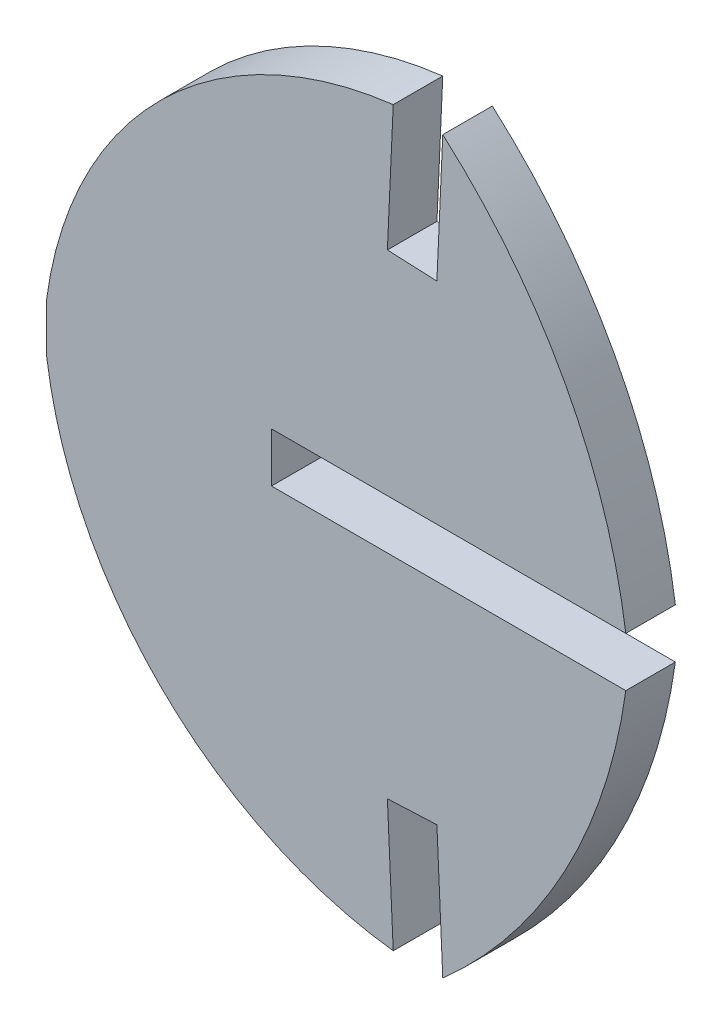
SolidWorks part; units mm, degrees
ref_plane "Front Plane" through (0, 0, 0) normal (0, 0, 1) x (1, 0, 0)
ref_plane "Top Plane" through (0, 0, 0) normal (0, 1, 0) x (1, 0, 0)
ref_plane "Right Plane" through (0, 0, 0) normal (1, 0, 0) x (0, 0, -1)
sketch "Sketch1" plane through (0, 0, 0) normal (0, 0, 1) x (1, 0, 0)
  line L0 (68.0534, 0) -> (68.0534, -1.524)
  line L1 (68.0534, -1.524) -> (68.0534, 0) construction
  line L2 (68.0534, -1.524) -> (78.9517, -1.524)
  line L3 (61.1383, -1.524) -> (61.1383, 0)
  line L4 (73.322, -11.994) -> (73.1412, -8.002)
  line L5 (71.7982, -12.0318) -> (71.6187, -8.071)
  line L6 (61.1383, -1.524) -> (61.1383, 0) construction
  line L7 (73.1412, -8.002) -> (71.6187, -8.071)
  line L8 (57.5926, -0.762) -> (45.737, -0.762) construction
  line L9 (73.1412, 6.478) -> (71.6187, 6.547)
  line L10 (71.7982, 10.5078) -> (71.6187, 6.547)
  line L11 (73.322, 10.47) -> (73.1412, 6.478)
  line L12 (68.0534, 0) -> (78.9517, 0)
  arc A0 (78.9517, -1.524) -> (73.322, -11.994) centre (62.0386, 0.8215) cw
  arc A1 (61.1383, -1.524) -> (71.7982, -12.0318) centre (73.2589, 0.111) ccw
  arc A2 (61.1383, 0) -> (71.7982, 10.5078) centre (73.2589, -1.635) cw
  arc A3 (78.9517, 0) -> (73.322, 10.47) centre (62.0386, -2.3455) ccw
  point P27 (61.1383, -0.762)
  point P28 (68.0534, -0.762)
extrude "Boss-Extrude1" add sketch "Sketch1" along normal blind 1.524
